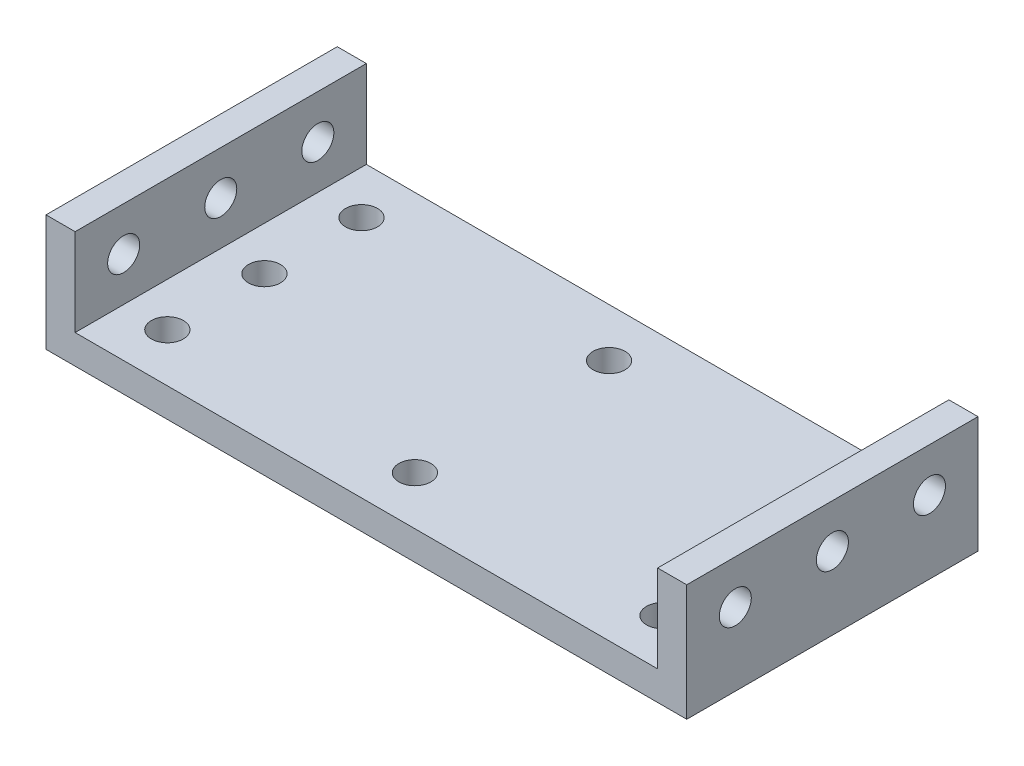
SolidWorks part; units mm, degrees
ref_plane "正面" through (0, 0, 0) normal (0, 0, 1) x (1, 0, 0)
ref_plane "平面" through (0, 0, 0) normal (0, 1, 0) x (1, 0, 0)
ref_plane "右側面" through (0, 0, 0) normal (1, 0, 0) x (0, 0, -1)
sketch "ｽｹｯﾁ1" plane through (0, 0, 0) normal (0, 0, 1) x (1, 0, 0)
  line L0 (0, 0) -> (0, 9)
  line L1 (0, 9) -> (-3, 9)
  line L2 (-3, 9) -> (-3, -3)
  line L3 (-3, -3) -> (63, -3)
  line L4 (63, -3) -> (63, 9)
  line L5 (63, 9) -> (60, 9)
  line L6 (60, 9) -> (60, 0)
  line L7 (60, 0) -> (0, 0)
  dimension "D1" = 3
  dimension "D2" = 3
  dimension "D3" = 66
  dimension "D4" = 9
  dimension "D5" = 12
extrude "ﾎﾞｽ - 押し出し1" add sketch "ｽｹｯﾁ1" along normal blind 30
sketch "ｽｹｯﾁ2" plane through (63, 0, 0) normal (1, 0, 0) x (0, 0, -1)
  line L0 (-30, 4.5) -> (0, 4.5) construction
  line L1 (-30, -3) -> (-30, 9) construction
  line L2 (0, -3) -> (0, 9) construction
  line L3 (-30, 9) -> (0, 9) construction
  circle A0 centre (-25, 4.5) radius 1.65
  circle A1 centre (-5, 4.5) radius 1.65
  circle A2 centre (-15, 4.5) radius 1.65
  dimension "D2" = 3.3
  dimension "D3" = 3.3
  dimension "D7" = 3.3
  dimension "D1" = 4.5
  dimension "D4" = 5
  dimension "D5" = 5
  dimension "D6" = 10
extrude "ｶｯﾄ - 押し出し1" cut sketch "ｽｹｯﾁ2" against normal through all
sketch "ｽｹｯﾁ3" plane through (0, 0, 0) normal (0, 1, 0) x (1, 0, 0)
  line L0 (30, 0) -> (30, -30) construction
  line L1 (60, 0) -> (0, 0) construction
  line L2 (60, -30) -> (0, -30) construction
  circle A0 centre (30, -5) radius 1.65
  circle A1 centre (30, -25) radius 1.65
  dimension "D3" = 3.3
  dimension "D4" = 3.3
  dimension "D1" = 5
  dimension "D2" = 5
extrude "ｶｯﾄ - 押し出し2" cut sketch "ｽｹｯﾁ3" against normal up to next
sketch "ｽｹｯﾁ4" plane through (0, 0, 0) normal (0, 1, 0) x (1, 0, 0)
  line L0 (63, -5) -> (-3, -5) construction
  line L1 (63, -30) -> (63, 0) construction
  line L2 (-3, -30) -> (-3, 0) construction
  line L3 (63, -15) -> (-3, -15) construction
  line L4 (63, -25) -> (-3, -25) construction
  line L5 (60, 0) -> (0, 0) construction
  line L6 (60, -30) -> (0, -30) construction
  line L7 (4.5, 0) -> (4.5, -30) construction
  line L8 (55.5, 0) -> (55.5, -30) construction
  line L9 (0, -30) -> (0, 0) construction
  line L10 (60, -30) -> (60, 0) construction
  circle A0 centre (4.5, -5) radius 1.65
  circle A1 centre (4.5, -15) radius 1.65
  circle A2 centre (4.5, -25) radius 1.65
  circle A3 centre (55.5, -25) radius 1.65
  circle A4 centre (55.5, -15) radius 1.65
  circle A5 centre (55.5, -5) radius 1.65
  dimension "D5" = 3.3
  dimension "D1" = 5
  dimension "D2" = 5
  dimension "D3" = 4.5
  dimension "D4" = 4.5
extrude "ｶｯﾄ - 押し出し3" cut sketch "ｽｹｯﾁ4" against normal up to next
